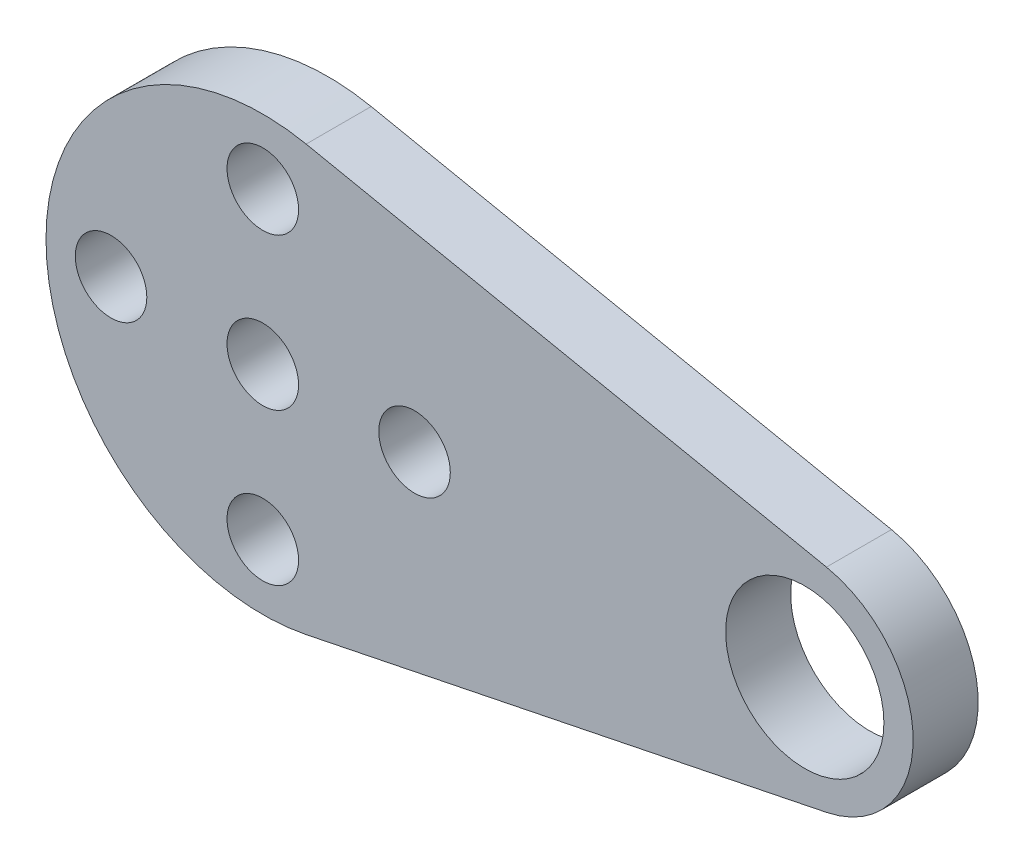
SolidWorks part; units mm, degrees
ref_plane "前视基准面" through (0, 0, 0) normal (0, 0, 1) x (1, 0, 0)
ref_plane "上视基准面" through (0, 0, 0) normal (0, 1, 0) x (1, 0, 0)
ref_plane "右视基准面" through (0, 0, 0) normal (1, 0, 0) x (0, 0, -1)
sketch "草图1" plane through (0, 0, 0) normal (0, 0, 1) x (1, 0, 0)
  line L0 (20, 10) -> (20, 0)
  line L2 (0, 0) -> (0, 10)
  line L4 (110, 0) -> (110, 10)
  line L5 (8.4007, 15.5327) -> (43.2842, 8.4121)
  line L6 (20, 5) -> (35, 5)
  line L7 (40, 10) -> (40, 0)
  line L8 (8.4007, -5.5327) -> (43.2842, 1.5879)
  circle A0 centre (10, 5) radius 10
  circle A1 centre (10, 12) radius 1.65
  circle A2 centre (17, 5) radius 1.65
  circle A3 centre (3, 5) radius 1.65
  circle A4 centre (10, -2) radius 1.65
  circle A5 centre (10, 5) radius 1.65
  circle A6 centre (35, 5) radius 3.65
  circle A7 centre (35, 5) radius 5
  dimension "D1" = 70
  dimension "D2" = 75
extrude "凸台-拉伸1" add sketch "草图1" along normal blind 3
